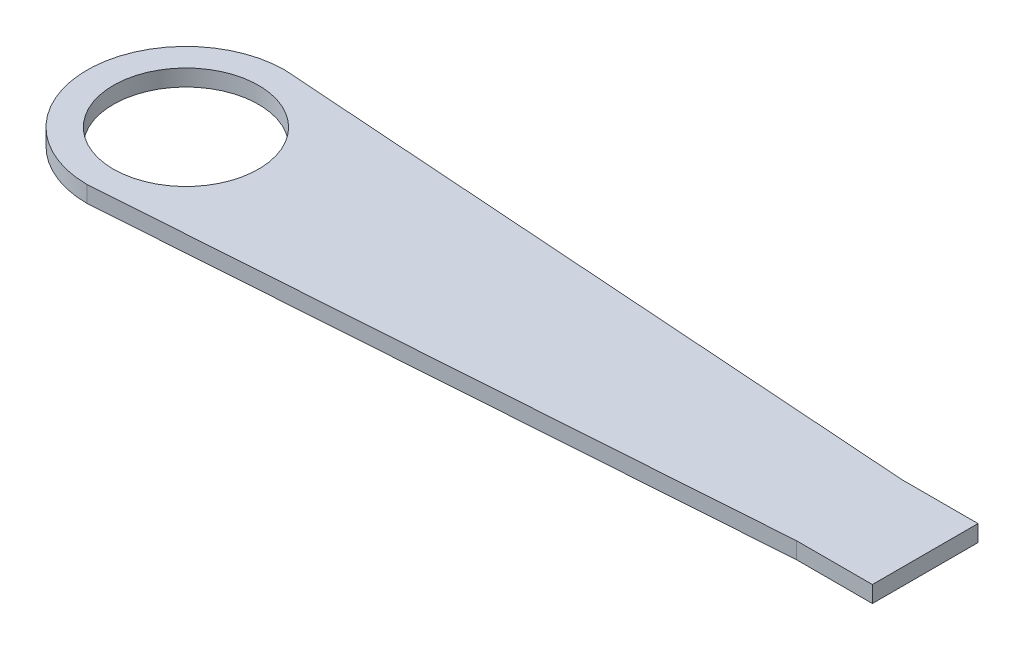
SolidWorks part; units mm, degrees
ref_plane "Front Plane" through (0, 0, 0) normal (0, 0, 1) x (1, 0, 0)
ref_plane "Top Plane" through (0, 0, 0) normal (0, 1, 0) x (1, 0, 0)
ref_plane "Right Plane" through (0, 0, 0) normal (1, 0, 0) x (0, 0, -1)
sketch "Sketch1" plane through (0, 0, 0) normal (0, 1, 0) x (1, 0, 0)
  line L0 (-3.1503, 1.9955) -> (6.8975, 1.2955)
  line L1 (-4.6503, 1.2955) -> (8.0497, 1.2955)
  line L2 (-4.6503, 1.2955) -> (-4.6503, -0.3045)
  line L3 (-4.6503, -0.3045) -> (8.0497, -0.3045)
  line L4 (8.0497, 1.2955) -> (8.0497, -0.3045)
  line L5 (6.8975, 1.2955) -> (6.8975, -0.3045)
  line L6 (6.8975, -0.3045) -> (-3.1503, -1.0045)
  circle A0 centre (-3.1503, 0.4955) radius 1.5
  circle A2 centre (-3.1503, 0.4955) radius 1.1
  dimension "D3" = 0.8
  dimension "D1" = 12.7
  dimension "D2" = 1.6
  dimension "D4" = 1.5
extrude "Boss-Extrude3" add sketch "Sketch1" along normal blind 0.25 contours A2 L1 A0 L0 | A0 L1 L0 | A2 L1 A0 L3 | A2 L3 A0 L1 | A2 L3 A0 L6 | A0 L3 L5 L1 | A0 L6 L3 | L1 L5 L3 L4
